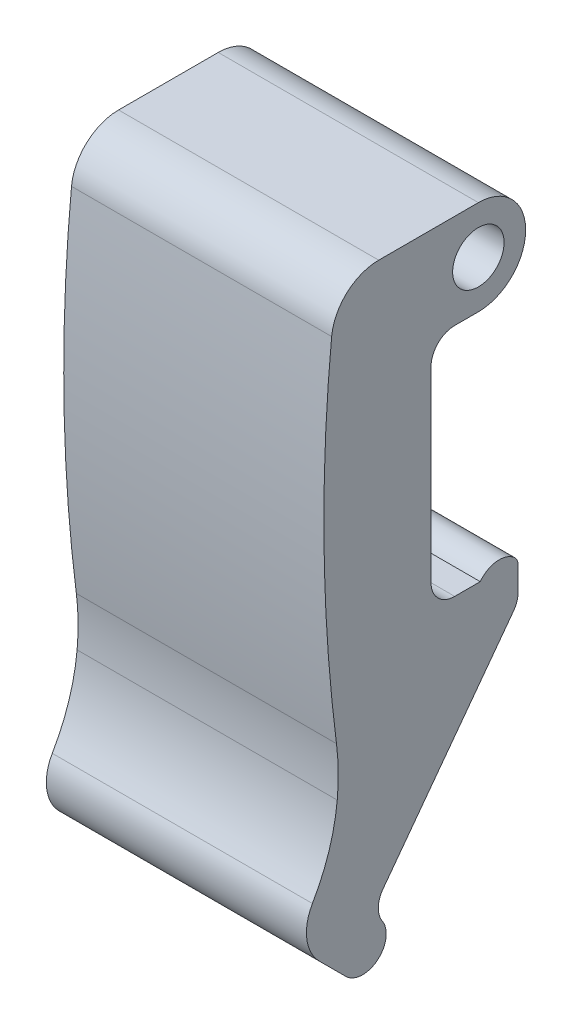
SolidWorks part; units mm, degrees
material "PP Copolymer"
ref_plane "Front" through (0, 0, 0) normal (0, 0, 1) x (1, 0, 0)
ref_plane "Top" through (0, 0, 0) normal (0, 1, 0) x (1, 0, 0)
ref_plane "Right" through (0, 0, 0) normal (1, 0, 0) x (0, 0, -1)
sketch "Sketch1" plane through (0, 0, 0) normal (1, 0, 0) x (0, 0, -1)
  line L0 (0, 3.175) -> (-9.525, 3.175)
  line L1 (0, -3.175) -> (-3.175, -3.175)
  line L2 (-3.175, -3.175) -> (-3.175, -18.923)
  line L3 (-3.175, -18.923) -> (0.127, -18.923)
  line L4 (2.667, -18.923) -> (2.667, -21.336)
  line L5 (2.667, -21.336) -> (-7.1882, -34.5819)
  line L6 (-7.1882, -34.5819) -> (-6.6494, -35.1208)
  line L7 (-7.1882, -34.5819) -> (-1.524, -34.5819) construction
  line L8 (-7.7719, -36.2433) -> (-5.0608, -38.9544) construction
  line L9 (-9.4333, -36.827) -> (-8.8944, -37.3658)
  line L10 (-9.4333, -36.827) -> (-10.6751, -35.5851)
  arc A0 (0, -3.175) -> (0, 3.175) centre (0, 0) ccw
  arc A1 (0.127, -18.923) -> (2.667, -18.923) centre (1.397, -19.8755) cw
  arc A2 (-6.6494, -35.1208) -> (-8.8944, -37.3658) centre (-7.7719, -36.2433) cw
  arc A3 (-9.525, 3.175) -> (-9.525, -23.5148) centre (95.2741, -10.1699) ccw
  arc A4 (-10.6751, -35.5851) -> (-10.6551, -31.3781) centre (-8.5816, -33.4915) cw
  arc A5 (-9.525, -23.5148) -> (-10.6551, -31.3781) centre (-24.3294, -25.4) cw
  dimension "D1" = 6.35
  dimension "D2" = 6.35
  dimension "D5" = 0.635
  dimension "D7" = 3.048
  dimension "D10" = 12.7
  dimension "D13" = 1.5875
  dimension "D3" = 15.748
  dimension "D4" = 3.302
  dimension "D6" = 2.54
  dimension "D8" = 16.51
  dimension "D9" = 9.8552
  dimension "D11" = 45
  dimension "D12" = 0.762
  dimension "D14" = 28.575
extrude "Extrude1" add sketch "Sketch1" along normal mid plane 17.4625
fillet "Fillet1" radius 3.175 1 edges at (0, 3.175, 9.525)
fillet "Fillet2" radius 1.5875 4 edges at (0, -3.175, 3.175) (0, -34.5819, 7.1882) (0, -21.336, -2.667) (0, -18.923, 3.175)
fillet "Fillet3" radius 12.7 1 edges at (0, -31.3781, 10.6551)
fillet "Fillet5" radius 0.7937 1 edges at (0, -18.923, -2.667)
hole_wizard "#29 (0.136) Diameter Hole1" positions "Sketch3" profile "Sketch2" hole size "#29" standard "Ansi Inch" end condition through all
sketch "Sketch3" plane through (8.7312, 0, 0) normal (1, 0, 0) x (0, 0, -1)
  point P0 (0, 0)
sketch "Sketch2" plane through (8.7312, 0, 0) normal (0, 1, 0) x (0, 0, -1)
  line L0 (0, 0) -> (0, 17.4625)
  line L1 (0, 17.4625) -> (1.7272, 17.4625)
  line L2 (1.7272, 17.4625) -> (1.7272, 0)
  line L5 (1.7272, 0) -> (0, 0)
  line L11 (0, -6.35) -> (0, 107.95) construction
  dimension "Thru Hole Dia." = 3.4544
  dimension "Thru Hole Depth" = 17.4625
